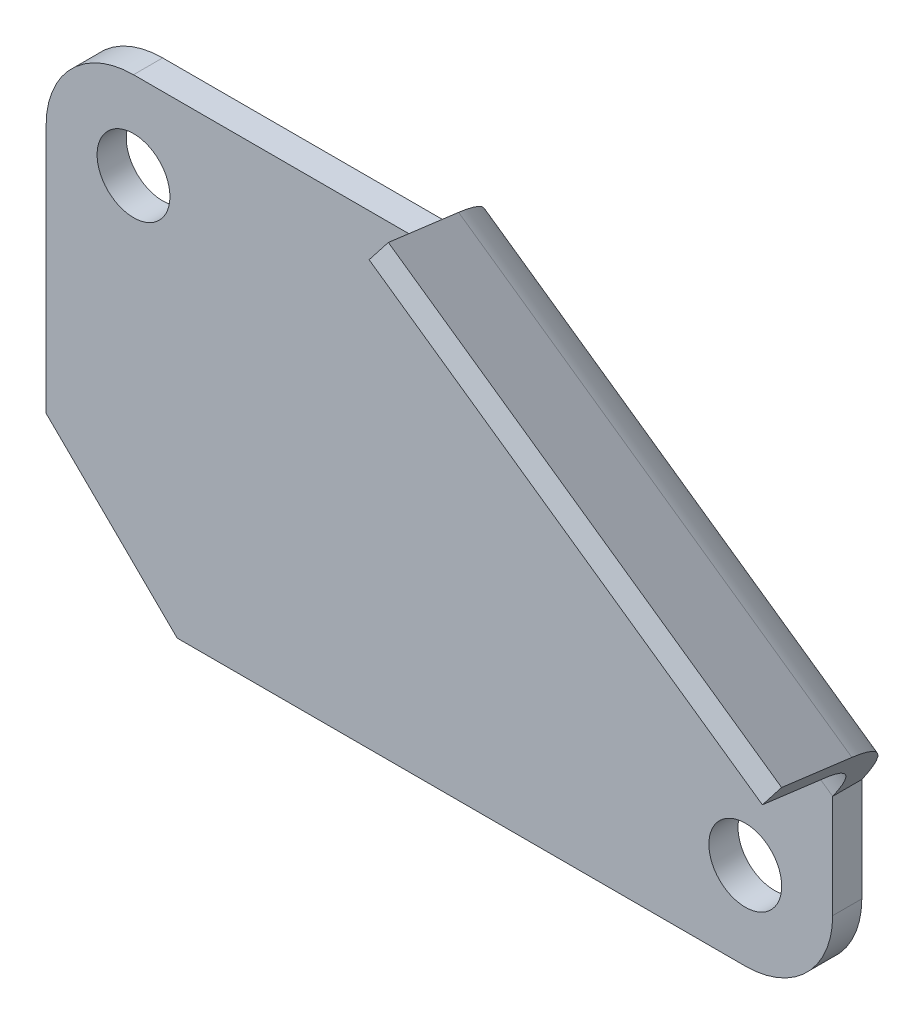
SolidWorks part; units mm, degrees
material "Manganese Bronze"
ref_plane "Front Plane" through (0, 0, 0) normal (0, 0, 1) x (1, 0, 0)
ref_plane "Top Plane" through (0, 0, 0) normal (0, 1, 0) x (1, 0, 0)
ref_plane "Right Plane" through (0, 0, 0) normal (1, 0, 0) x (0, 0, -1)
sketch "Sketch1" plane through (0, 0, 0) normal (0, 0, 1) x (1, 0, 0)
  line L0 (11793.2786, 63786.1363) -> (53793.2786, 63786.1363)
  line L1 (107793.2786, 25974.9292) -> (107793.2786, 11786.1363)
  line L2 (95793.2786, -213.8637) -> (17793.2786, -213.8637)
  line L3 (-206.7214, 17513.7858) -> (-206.7214, 51786.1363)
  line L4 (-206.7214, 17513.7858) -> (17793.2786, -213.8637)
  line L9 (53793.2786, 63786.1363) -> (107793.2786, 25974.9292)
  arc A0 (107793.2786, 11786.1363) -> (95793.2786, -213.8637) centre (95793.2786, 11786.1363) cw
  arc A1 (11793.2786, 63786.1363) -> (-206.7214, 51786.1363) centre (11793.2786, 51786.1363) ccw
  circle A2 centre (11793.2786, 51786.1363) radius 5000
  circle A3 centre (95793.2786, 11786.1363) radius 5000
  dimension "D1" = 12000
  dimension "D2" = 35
extrude "Boss-Extrude1" add sketch "Sketch1" along normal blind 4000
ref_plane "Plane1" through (60126.151, -42100.7842, 0) normal (0.8192, -0.5736, 0) x (0, 0, -1)
sketch "Sketch5" plane through (60126.151, -42100.7842, 0) normal (0.8192, -0.5736, 0) x (0, 0, -1)
  line L0 (-4000, 83105.101) -> (0, 83105.101)
  line L1 (-10602.6463, 93822.7767) -> (-22572.2467, 98658.8092)
  line L2 (-9100.464, 96597.0937) -> (-21662.3807, 101672.4375)
  line L3 (-22572.2467, 98658.8092) -> (-21662.3807, 101672.4375)
  line L4 (-4000, 71482.3222) -> (-4000, 83105.101) construction
  arc A0 (-4000, 83105.101) -> (-10602.6463, 93822.7767) centre (-16000, 83105.101) ccw
  arc A1 (0, 83105.101) -> (-9100.464, 96597.0937) centre (-14551.5829, 83105.101) ccw
  point P8 (0, 0)
  point P11 (-7816.2021, 96028.6715)
  point P12 (0, 0)
  point P13 (0, 0)
  point P14 (0, 0)
  point P15 (0, 0)
  point P16 (0, 0)
  point P17 (0, 0)
  point P18 (0, 0)
  point P19 (0, 0)
  point P20 (0, 0)
  point P21 (-7193.743, 97006.4527)
  point P22 (-8322.9057, 96256.2281)
  point P23 (0, 0)
  point P24 (-22339.4487, 99199.208)
  point P25 (0, 0)
  point P26 (0, 0)
  point P27 (-19680.4185, 102829.9184)
  point P28 (-20527.2854, 102068.2339)
  dimension "D1" = 112
  dimension "D2" = 112
extrude "Boss-Extrude2" add sketch "Sketch5" against normal up to vertex (65921.8278 mm away) up to point (53793.2786, 63786.1362, 4000)
